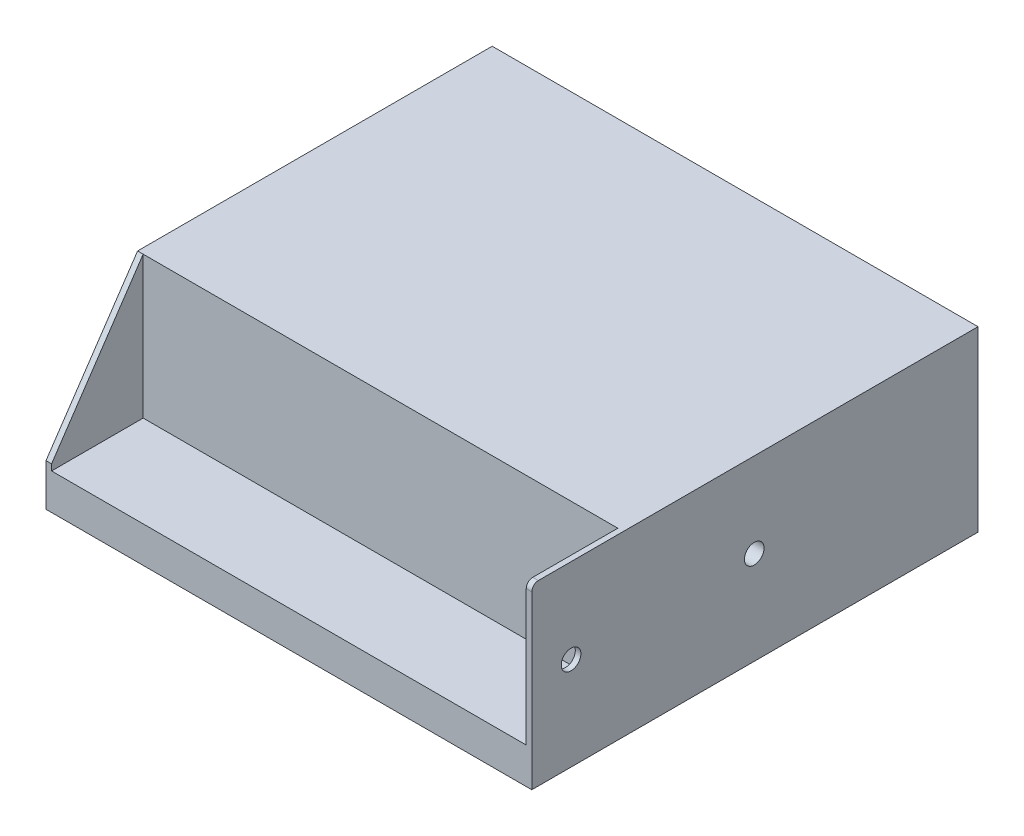
SolidWorks part; units mm, degrees
ref_plane "Front Plane" through (0, 0, 0) normal (0, 0, 1) x (1, 0, 0)
ref_plane "Top Plane" through (0, 0, 0) normal (0, 1, 0) x (1, 0, 0)
ref_plane "Right Plane" through (0, 0, 0) normal (1, 0, 0) x (0, 0, -1)
sketch "Sketch1" plane through (0, 0, 0) normal (0, 1, 0) x (1, 0, 0)
  line L1 (37.125, -34.1) -> (-37.125, -34.1)
  line L2 (37.125, -34.1) -> (37.125, 34.1)
  line L3 (37.125, 34.1) -> (-37.125, 34.1)
  line L4 (-37.125, -34.1) -> (-37.125, 34.1)
  line L5 (37.125, -34.1) -> (-37.125, 34.1) construction
  line L6 (37.125, 34.1) -> (-37.125, -34.1) construction
  point P0 (0, 0)
  dimension "D1" = 74.25
  dimension "D2" = 68.2
extrude "Boss-Extrude1" add sketch "Sketch1" along normal blind 27.2
sketch "Sketch2" plane through (37.125, 0, 0) normal (1, 0, 0) x (0, 0, -1)
  line L0 (-28.1, 14.25) -> (-0.1, 14.25) construction
  line L1 (-34.1, 27.2) -> (-34.1, 0) construction
  line L2 (-34.1, 0) -> (34.1, 0) construction
  circle A0 centre (-28.1, 14.25) radius 1.5
  circle A1 centre (-0.1, 14.25) radius 1.5
  dimension "D1" = 3
  dimension "D2" = 6
  dimension "D3" = 34
  dimension "D4" = 14.25
extrude "Cut-Extrude1" cut sketch "Sketch2" against normal blind 10
sketch "Sketch3" plane through (0, 27.2, 0) normal (0, 1, 0) x (1, 0, 0)
  line L0 (-37.125, -34.1) -> (37.125, -34.1) construction
  line L1 (36.275, -34.1) -> (-36.275, -34.1)
  line L2 (36.275, -34.1) -> (36.275, -20.1)
  line L3 (36.275, -20.1) -> (-36.275, -20.1)
  line L4 (-36.275, -34.1) -> (-36.275, -20.1)
  line L6 (37.125, -34.1) -> (37.125, 34.1) construction
  line L7 (-37.125, 34.1) -> (-37.125, -34.1) construction
  point P6 (-35.3818, -20.1)
  point P10 (0, 0)
  dimension "D1" = 14
  dimension "D2" = 0.85
  dimension "D3" = 0.85
extrude "Cut-Extrude2" cut sketch "Sketch3" against normal offset from surface (21.7 mm away) 5.5 up to face at (0, 0, 0)
chamfer "Chamfer1" distance 14 angle 56 1 edges at (-36.7, 27.2, 34.1)
fillet "Fillet1" radius 1 1 edges at (36.7, 27.2, 34.1)
sketch "Sketch4" plane through (0, 0, 0) normal (0, -1, 0) x (1, 0, 0)
  line L1 (37.125, -34.1) -> (-37.125, -34.1) construction
  circle A0 centre (0, -30.1) radius 1.5
  circle A1 centre (0, 19.9) radius 1.5
  point P4 (0, 0)
  point P5 (-9.6132, 19.9)
  dimension "D1" = 3
  dimension "D3" = 4
  dimension "D2" = 54
extrude "Cut-Extrude3" cut sketch "Sketch4" against normal blind 2
